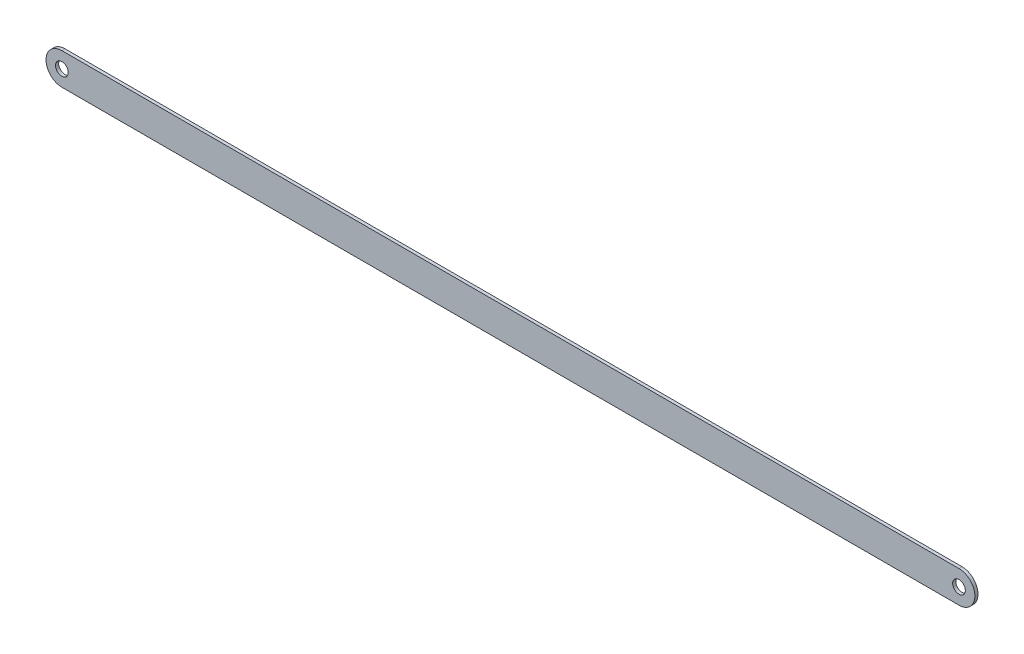
SolidWorks part; units mm, degrees
ref_plane "Front Plane" through (0, 0, 0) normal (0, 0, 1) x (1, 0, 0)
ref_plane "Top Plane" through (0, 0, 0) normal (0, 1, 0) x (1, 0, 0)
ref_plane "Right Plane" through (0, 0, 0) normal (1, 0, 0) x (0, 0, -1)
sketch "Sketch1" plane through (0, 0, 0) normal (0, 0, 1) x (1, 0, 0)
  line L0 (0, 0) -> (287.02, 0)
  line L1 (287.02, 10.16) -> (0, 10.16)
  arc A0 (287.02, 0) -> (287.02, 10.16) centre (287.02, 5.08) ccw
  arc A1 (0, 10.16) -> (0, 0) centre (0, 5.08) ccw
  dimension "D1" = 10.16
  dimension "D2" = 287.02
extrude "Boss-Extrude1" add sketch "Sketch1" along normal mid plane 1
sketch "Sketch2" plane through (0, 0, 0.5) normal (0, 0, 1) x (1, 0, 0)
  circle A0 centre (0, 5.08) radius 2.032
  circle A1 centre (287.02, 5.08) radius 2.0267
  dimension "D1" = 4.064
  dimension "D2" = 4.0535
extrude "Cut-Extrude1" cut sketch "Sketch2" against normal blind 2.54
